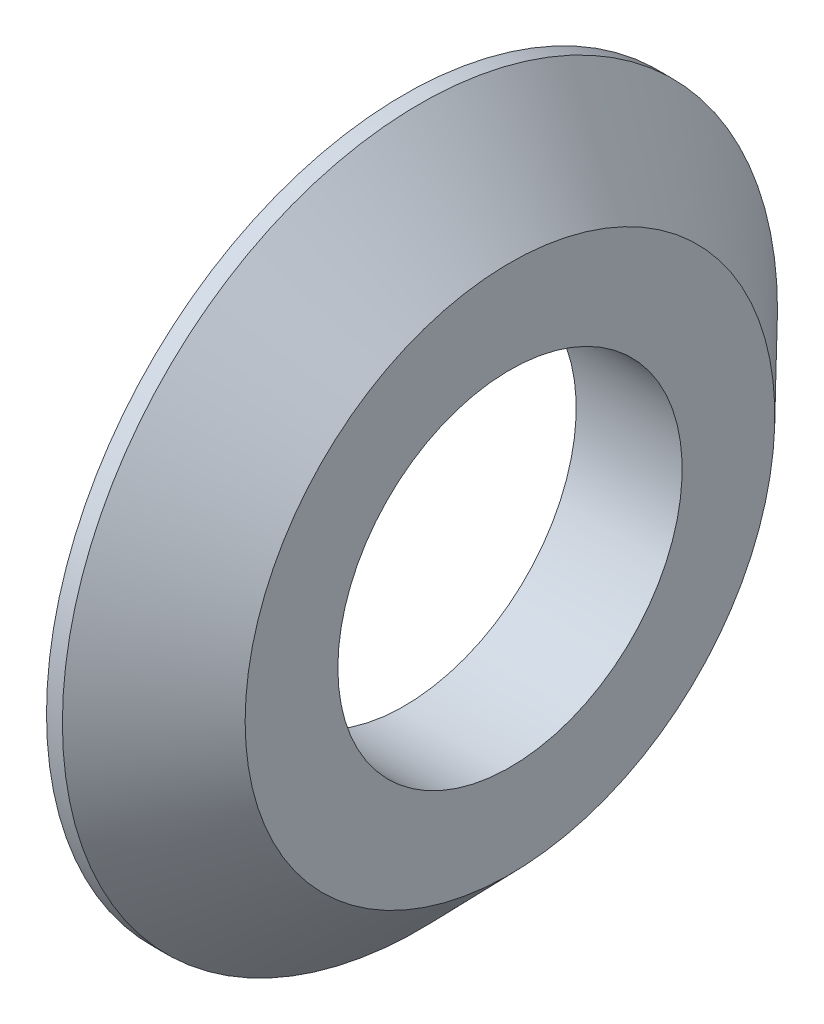
SolidWorks part; units mm, degrees
ref_plane "Front Plane" through (0, 0, 0) normal (0, 0, 1) x (1, 0, 0)
ref_plane "Top Plane" through (0, 0, 0) normal (0, 1, 0) x (1, 0, 0)
ref_plane "Right Plane" through (0, 0, 0) normal (1, 0, 0) x (0, 0, -1)
sketch "Sketch1" plane through (0, 0, 0) normal (0, 1, 0) x (1, 0, 0)
  line L0 (-6.2551, 0) -> (5.6318, 0) construction
  line L1 (-1, 3.25) -> (1, 3.25)
  line L2 (-1, 3.25) -> (-1, 6.75)
  line L3 (-1, 6.75) -> (-0.7, 6.75)
  line L4 (-0.7, 6.75) -> (1, 5)
  line L5 (1, 5) -> (1, 3.25)
  point P5 (0, 3.25)
  dimension "D1" = 3.25
  dimension "D2" = 2
  dimension "D3" = 5
  dimension "D4" = 0.3
  dimension "D5" = 6.75
revolve "Revolve1" add sketch "Sketch1" angle 360 about L0
